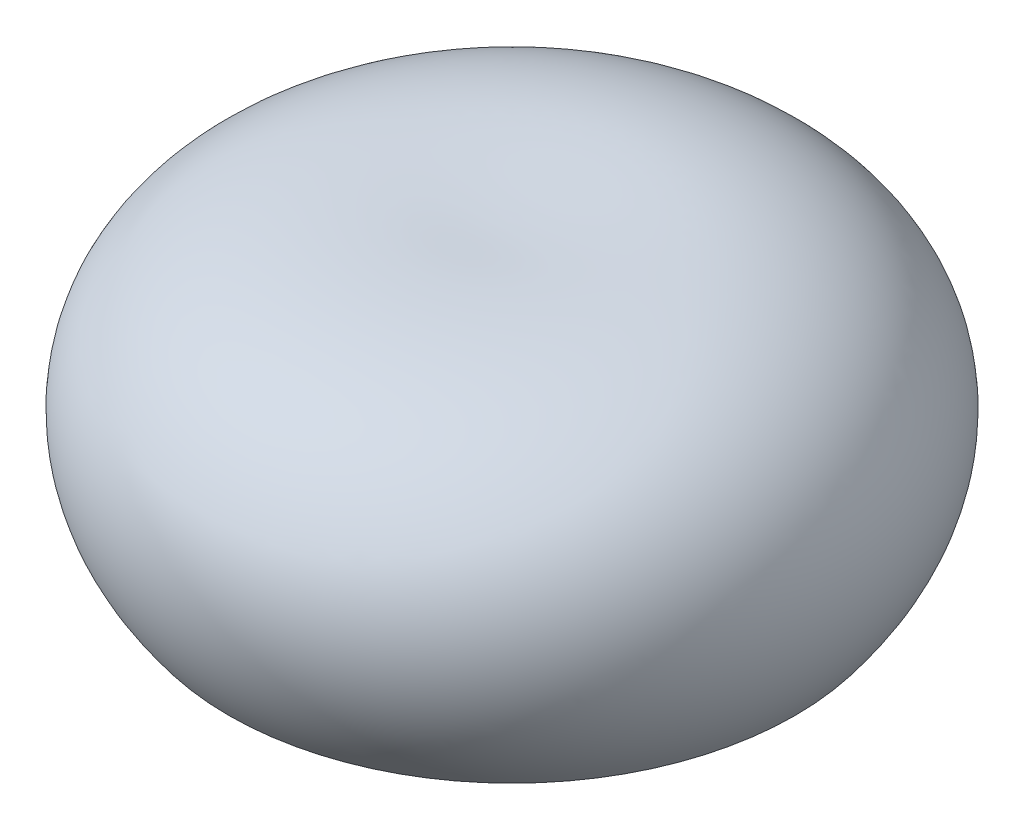
SolidWorks part; units mm, degrees
ref_plane "前视基准面" through (0, 0, 0) normal (0, 0, 1) x (1, 0, 0)
ref_plane "上视基准面" through (0, 0, 0) normal (0, 1, 0) x (1, 0, 0)
ref_plane "右视基准面" through (0, 0, 0) normal (1, 0, 0) x (0, 0, -1)
curve "曲线1"
  spline degree 3 poles (0, 7, 0) (0.0738, 6.9996, 0) (0.1783, 6.9991, 0) (0.3064, 7.0012, 0) (0.3805, 7.0029, 0) (0.4416, 7.0045, 0) (0.495, 7.0061, 0) (0.5432, 7.0077, 0) (0.5875, 7.0093, 0) (0.6288, 7.0109, 0) (0.6676, 7.0125, 0) (0.7044, 7.0141, 0) (0.7394, 7.0157, 0) (0.7729, 7.0172, 0) (0.8051, 7.0187, 0) (0.8362, 7.0203, 0) (0.8662, 7.0218, 0) (0.8953, 7.0233, 0) (0.9235, 7.0247, 0) (0.951, 7.0262, 0) (0.9778, 7.0276, 0) (1.004, 7.0291, 0) (1.0295, 7.0305, 0) (1.0545, 7.0319, 0) (1.079, 7.0333, 0) (1.103, 7.0346, 0) (1.1265, 7.036, 0) (1.1496, 7.0373, 0) (1.1724, 7.0386, 0) (1.1947, 7.0399, 0) (1.2167, 7.0412, 0) (1.2384, 7.0425, 0) (1.2598, 7.0438, 0) (1.2808, 7.045, 0) (1.3016, 7.0462, 0) (1.3221, 7.0474, 0) (1.3423, 7.0486, 0) (1.3623, 7.0498, 0) (1.382, 7.051, 0) (1.4015, 7.0521, 0) (1.4208, 7.0533, 0) (1.4399, 7.0544, 0) (1.4588, 7.0555, 0) (1.4775, 7.0566, 0) (1.496, 7.0577, 0) (1.5143, 7.0587, 0) (1.5324, 7.0598, 0) (1.5504, 7.0608, 0) (1.5682, 7.0618, 0) (1.5859, 7.0628, 0) (1.6034, 7.0638, 0) (1.6207, 7.0648, 0) (1.6379, 7.0657, 0) (1.655, 7.0667, 0) (1.672, 7.0676, 0) (1.6888, 7.0685, 0) (1.7054, 7.0694, 0) (1.722, 7.0703, 0) (1.7385, 7.0712, 0) (1.7548, 7.072, 0) (1.771, 7.0728, 0) (1.7871, 7.0737, 0) (1.8031, 7.0745, 0) (1.819, 7.0753, 0) (1.8348, 7.0761, 0) (1.8505, 7.0768, 0) (1.8661, 7.0776, 0) (1.8816, 7.0783, 0) (1.897, 7.079, 0) (1.9123, 7.0797, 0) (1.9275, 7.0804, 0) (1.9427, 7.0811, 0) (1.9578, 7.0818, 0) (1.9727, 7.0824, 0) (1.9876, 7.0831, 0) (2.0025, 7.0837, 0) (2.0172, 7.0843, 0) (2.0319, 7.0849, 0) (2.0465, 7.0855, 0) (2.061, 7.0861, 0) (2.0755, 7.0866, 0) (2.0899, 7.0872, 0) (2.1042, 7.0877, 0) (2.1184, 7.0882, 0) (2.1326, 7.0887, 0) (2.1468, 7.0892, 0) (2.1608, 7.0896, 0) (2.1748, 7.0901, 0) (2.1888, 7.0905, 0) (2.2027, 7.091, 0) (2.2165, 7.0914, 0) (2.2302, 7.0918, 0) (2.244, 7.0922, 0) (2.2576, 7.0925, 0) (2.2712, 7.0929, 0) (2.2848, 7.0933, 0) (2.2983, 7.0936, 0) (2.3117, 7.0939, 0) (2.3251, 7.0942, 0) (2.3385, 7.0945, 0) (2.3518, 7.0948, 0) (2.365, 7.095, 0) (2.3782, 7.0953, 0) (2.3914, 7.0955, 0) (2.4045, 7.0958, 0) (2.4175, 7.096, 0) (2.4305, 7.0962, 0) (2.4435, 7.0964, 0) (2.4565, 7.0965, 0) (2.4693, 7.0967, 0) (2.4822, 7.0968, 0) (2.495, 7.097, 0) (2.5078, 7.0971, 0) (2.5205, 7.0972, 0) (2.5332, 7.0973, 0) (2.5458, 7.0974, 0) (2.5584, 7.0974, 0) (2.571, 7.0975, 0) (2.5835, 7.0975, 0) (2.596, 7.0975, 0) (2.6085, 7.0975, 0) (2.6209, 7.0975, 0) (2.6333, 7.0975, 0) (2.6457, 7.0975, 0) (2.658, 7.0975, 0) (2.6703, 7.0974, 0) (2.6825, 7.0973, 0) (2.6948, 7.0973, 0) (2.7069, 7.0972, 0) (2.7191, 7.0971, 0) (2.7312, 7.0969, 0) (2.7433, 7.0968, 0) (2.7554, 7.0967, 0) (2.7674, 7.0965, 0) (2.7794, 7.0963, 0) (2.7914, 7.0962, 0) (2.8033, 7.096, 0) (2.8152, 7.0958, 0) (2.8271, 7.0955, 0) (2.8389, 7.0953, 0) (2.8508, 7.095, 0) (2.8625, 7.0948, 0) (2.8743, 7.0945, 0) (2.8861, 7.0942, 0) (2.8978, 7.0939, 0) (2.9094, 7.0936, 0) (2.9211, 7.0933, 0) (2.9327, 7.093, 0) (2.9443, 7.0926, 0) (2.9559, 7.0922, 0) (2.9675, 7.0919, 0) (2.979, 7.0915, 0) (2.9905, 7.0911, 0) (3.002, 7.0907, 0) (3.0134, 7.0902, 0) (3.0249, 7.0898, 0) (3.0363, 7.0893, 0) (3.0477, 7.0889, 0) (3.059, 7.0884, 0) (3.0704, 7.0879, 0) (3.0817, 7.0874, 0) (3.093, 7.0869, 0) (3.1042, 7.0864, 0) (3.1155, 7.0858, 0) (3.1267, 7.0853, 0) (3.1379, 7.0847, 0) (3.1491, 7.0841, 0) (3.1602, 7.0835, 0) (3.1714, 7.0829, 0) (3.1825, 7.0823, 0) (3.1936, 7.0817, 0) (3.2047, 7.0811, 0) (3.2157, 7.0804, 0) (3.2267, 7.0797, 0) (3.2378, 7.0791, 0) (3.2488, 7.0784, 0) (3.2597, 7.0777, 0) (3.2707, 7.0769, 0) (3.2816, 7.0762, 0) (3.2925, 7.0755, 0) (3.3034, 7.0747, 0) (3.3143, 7.074, 0) (3.3252, 7.0732, 0) (3.336, 7.0724, 0) (3.3468, 7.0716, 0) (3.3576, 7.0708, 0) (3.3684, 7.0699, 0) (3.3792, 7.0691, 0) (3.3899, 7.0683, 0) (3.4006, 7.0674, 0) (3.4113, 7.0665, 0) (3.422, 7.0656, 0) (3.4327, 7.0647, 0) (3.4434, 7.0638, 0) (3.454, 7.0629, 0) (3.4646, 7.0619, 0) (3.4752, 7.061, 0) (3.4858, 7.06, 0) (3.4964, 7.059, 0) (3.507, 7.0581, 0) (3.5175, 7.0571, 0) (3.528, 7.056, 0) (3.5385, 7.055, 0) (3.549, 7.054, 0) (3.5595, 7.0529, 0) (3.5699, 7.0519, 0) (3.5804, 7.0508, 0) (3.5908, 7.0497, 0) (3.6012, 7.0486, 0) (3.6116, 7.0475, 0) (3.622, 7.0464, 0) (3.6324, 7.0452, 0) (3.6427, 7.0441, 0) (3.6531, 7.0429, 0) (3.6634, 7.0417, 0) (3.6737, 7.0406, 0) (3.684, 7.0394, 0) (3.6942, 7.0381, 0) (3.7045, 7.0369, 0) (3.7148, 7.0357, 0) (3.725, 7.0344, 0) (3.7352, 7.0332, 0) (3.7454, 7.0319, 0) (3.7556, 7.0306, 0) (3.7658, 7.0293, 0) (3.7759, 7.028, 0) (3.7861, 7.0267, 0) (3.7962, 7.0254, 0) (3.8063, 7.024, 0) (3.8164, 7.0227, 0) (3.8265, 7.0213, 0) (3.8366, 7.0199, 0) (3.8467, 7.0185, 0) (3.8567, 7.0171, 0) (3.8668, 7.0157, 0) (3.8768, 7.0142, 0) (3.8868, 7.0128, 0) (3.8968, 7.0113, 0) (3.9068, 7.0099, 0) (3.9168, 7.0084, 0) (3.9267, 7.0069, 0) (3.9367, 7.0054, 0) (3.9466, 7.0039, 0) (3.9565, 7.0024, 0) (3.9665, 7.0008, 0) (3.9764, 6.9993, 0) (3.9862, 6.9977, 0) (3.9961, 6.9961, 0) (4.006, 6.9945, 0) (4.0158, 6.9929, 0) (4.0257, 6.9913, 0) (4.0355, 6.9897, 0) (4.0453, 6.988, 0) (4.0551, 6.9864, 0) (4.0649, 6.9847, 0) (4.0747, 6.983, 0) (4.0844, 6.9813, 0) (4.0942, 6.9796, 0) (4.1039, 6.9779, 0) (4.1136, 6.9762, 0) (4.1234, 6.9745, 0) (4.1331, 6.9727, 0) (4.1428, 6.971, 0) (4.1524, 6.9692, 0) (4.1621, 6.9674, 0) (4.1718, 6.9656, 0) (4.1814, 6.9638, 0) (4.1911, 6.962, 0) (4.2007, 6.9601, 0) (4.2103, 6.9583, 0) (4.2199, 6.9564, 0) (4.2295, 6.9545, 0) (4.2391, 6.9527, 0) (4.2486, 6.9508, 0) (4.2582, 6.9488, 0) (4.2677, 6.9469, 0) (4.2773, 6.945, 0) (4.2868, 6.943, 0) (4.2963, 6.9411, 0) (4.3058, 6.9391, 0) (4.3153, 6.9371, 0) (4.3248, 6.9351, 0) (4.3343, 6.9331, 0) (4.3437, 6.9311, 0) (4.3532, 6.9291, 0) (4.3626, 6.927, 0) (4.3721, 6.925, 0) (4.3815, 6.9229, 0) (4.3909, 6.9208, 0) (4.4003, 6.9187, 0) (4.4097, 6.9166, 0) (4.4191, 6.9145, 0) (4.4284, 6.9123, 0) (4.4378, 6.9102, 0) (4.4471, 6.908, 0) (4.4565, 6.9059, 0) (4.4658, 6.9037, 0) (4.4751, 6.9015, 0) (4.4844, 6.8993, 0) (4.4937, 6.8971, 0) (4.503, 6.8948, 0) (4.5123, 6.8926, 0) (4.5215, 6.8903, 0) (4.5308, 6.8881, 0) (4.54, 6.8858, 0) (4.5493, 6.8835, 0) (4.5585, 6.8812, 0) (4.5677, 6.8789, 0) (4.5769, 6.8765, 0) (4.5861, 6.8742, 0) (4.5953, 6.8718, 0) (4.6045, 6.8695, 0) (4.6136, 6.8671, 0) (4.6228, 6.8647, 0) (4.6319, 6.8623, 0) (4.6411, 6.8599, 0) (4.6502, 6.8575, 0) (4.6593, 6.855, 0) (4.6684, 6.8526, 0) (4.6775, 6.8501, 0) (4.6866, 6.8476, 0) (4.6957, 6.8451, 0) (4.7048, 6.8426, 0) (4.7138, 6.8401, 0) (4.7229, 6.8376, 0) (4.7319, 6.835, 0) (4.741, 6.8325, 0) (4.75, 6.8299, 0) (4.759, 6.8273, 0) (4.768, 6.8247, 0) (4.777, 6.8221, 0) (4.786, 6.8195, 0) (4.795, 6.8169, 0) (4.8039, 6.8142, 0) (4.8129, 6.8116, 0) (4.8218, 6.8089, 0) (4.8308, 6.8062, 0) (4.8397, 6.8035, 0) (4.8486, 6.8008, 0) (4.8575, 6.7981, 0) (4.8664, 6.7954, 0) (4.8753, 6.7926, 0) (4.8842, 6.7899, 0) (4.8931, 6.7871, 0) (4.902, 6.7843, 0) (4.9108, 6.7815, 0) (4.9197, 6.7787, 0) (4.9285, 6.7759, 0) (4.9373, 6.7731, 0) (4.9462, 6.7702, 0) (4.955, 6.7673, 0) (4.9638, 6.7645, 0) (4.9726, 6.7616, 0) (4.9813, 6.7587, 0) (4.9901, 6.7558, 0) (4.9989, 6.7529, 0) (5.0076, 6.7499, 0) (5.0164, 6.747, 0) (5.0251, 6.744, 0) (5.0339, 6.7411, 0) (5.0426, 6.7381, 0) (5.0513, 6.7351, 0) (5.06, 6.7321, 0) (5.0687, 6.729, 0) (5.0774, 6.726, 0) (5.0861, 6.7229, 0) (5.0947, 6.7199, 0) (5.1034, 6.7168, 0) (5.112, 6.7137, 0) (5.1207, 6.7106, 0) (5.1293, 6.7075, 0) (5.1379, 6.7044, 0) (5.1465, 6.7012, 0) (5.1552, 6.6981, 0) (5.1638, 6.6949, 0) (5.1723, 6.6917, 0) (5.1809, 6.6885, 0) (5.1895, 6.6853, 0) (5.1981, 6.6821, 0) (5.2066, 6.6789, 0) (5.2151, 6.6756, 0) (5.2237, 6.6724, 0) (5.2322, 6.6691, 0) (5.2407, 6.6658, 0) (5.2492, 6.6625, 0) (5.2577, 6.6592, 0) (5.2662, 6.6559, 0) (5.2747, 6.6526, 0) (5.2832, 6.6492, 0) (5.2917, 6.6459, 0) (5.3001, 6.6425, 0) (5.3086, 6.6391, 0) (5.317, 6.6357, 0) (5.3254, 6.6323, 0) (5.3338, 6.6289, 0) (5.3423, 6.6254, 0) (5.3507, 6.622, 0) (5.3591, 6.6185, 0) (5.3674, 6.615, 0) (5.3758, 6.6115, 0) (5.3842, 6.608, 0) (5.3926, 6.6045, 0) (5.4009, 6.601, 0) (5.4092, 6.5974, 0) (5.4176, 6.5939, 0) (5.4259, 6.5903, 0) (5.4342, 6.5867, 0) (5.4425, 6.5831, 0) (5.4508, 6.5795, 0) (5.4591, 6.5759, 0) (5.4674, 6.5722, 0) (5.4757, 6.5686, 0) (5.4839, 6.5649, 0) (5.4922, 6.5612, 0) (5.5004, 6.5576, 0) (5.5087, 6.5538, 0) (5.5169, 6.5501, 0) (5.5251, 6.5464, 0) (5.5333, 6.5427, 0) (5.5415, 6.5389, 0) (5.5497, 6.5351, 0) (5.5579, 6.5313, 0) (5.5661, 6.5275, 0) (5.5743, 6.5237, 0) (5.5824, 6.5199, 0) (5.5906, 6.5161, 0) (5.5987, 6.5122, 0) (5.6069, 6.5083, 0) (5.615, 6.5045, 0) (5.6231, 6.5006, 0) (5.6312, 6.4967, 0) (5.6393, 6.4927, 0) (5.6474, 6.4888, 0) (5.6555, 6.4849, 0) (5.6635, 6.4809, 0) (5.6716, 6.4769, 0) (5.6796, 6.4729, 0) (5.6877, 6.4689, 0) (5.6957, 6.4649, 0) (5.7038, 6.4609, 0) (5.7118, 6.4568, 0) (5.7198, 6.4528, 0) (5.7278, 6.4487, 0) (5.7358, 6.4446, 0) (5.7438, 6.4405, 0) (5.7517, 6.4364, 0) (5.7597, 6.4323, 0) (5.7676, 6.4282, 0) (5.7756, 6.424, 0) (5.7835, 6.4198, 0) (5.7915, 6.4157, 0) (5.7994, 6.4115, 0) (5.8073, 6.4073, 0) (5.8152, 6.403, 0) (5.8231, 6.3988, 0) (5.831, 6.3945, 0) (5.8388, 6.3903, 0) (5.8467, 6.386, 0) (5.8546, 6.3817, 0) (5.8624, 6.3774, 0) (5.8703, 6.3731, 0) (5.8781, 6.3687, 0) (5.8859, 6.3644, 0) (5.8937, 6.36, 0) (5.9015, 6.3557, 0) (5.9093, 6.3513, 0) (5.9171, 6.3469, 0) (5.9249, 6.3424, 0) (5.9326, 6.338, 0) (5.9404, 6.3336, 0) (5.9481, 6.3291, 0) (5.9559, 6.3246, 0) (5.9636, 6.3201, 0) (5.9713, 6.3156, 0) (5.979, 6.3111, 0) (5.9867, 6.3066, 0) (5.9944, 6.302, 0) (6.0021, 6.2975, 0) (6.0098, 6.2929, 0) (6.0175, 6.2883, 0) (6.0251, 6.2837, 0) (6.0328, 6.2791, 0) (6.0404, 6.2745, 0) (6.048, 6.2698, 0) (6.0556, 6.2652, 0) (6.0633, 6.2605, 0) (6.0709, 6.2558, 0) (6.0784, 6.2511, 0) (6.086, 6.2464, 0) (6.0936, 6.2416, 0) (6.1012, 6.2369, 0) (6.1087, 6.2321, 0) (6.1163, 6.2274, 0) (6.1238, 6.2226, 0) (6.1313, 6.2178, 0) (6.1388, 6.2129, 0) (6.1463, 6.2081, 0) (6.1538, 6.2033, 0) (6.1613, 6.1984, 0) (6.1688, 6.1935, 0) (6.1763, 6.1886, 0) (6.1837, 6.1837, 0) (6.1912, 6.1788, 0) (6.1986, 6.1739, 0) (6.206, 6.1689, 0) (6.2134, 6.1639, 0) (6.2208, 6.159, 0) (6.2282, 6.154, 0) (6.2356, 6.1489, 0) (6.243, 6.1439, 0) (6.2504, 6.1389, 0) (6.2577, 6.1338, 0) (6.2651, 6.1287, 0) (6.2724, 6.1237, 0) (6.2798, 6.1186, 0) (6.2871, 6.1134, 0) (6.2944, 6.1083, 0) (6.3017, 6.1032, 0) (6.309, 6.098, 0) (6.3163, 6.0928, 0) (6.3235, 6.0876, 0) (6.3308, 6.0824, 0) (6.3381, 6.0772, 0) (6.3453, 6.072, 0) (6.3525, 6.0667, 0) (6.3598, 6.0615, 0) (6.367, 6.0562, 0) (6.3742, 6.0509, 0) (6.3814, 6.0456, 0) (6.3885, 6.0403, 0) (6.3957, 6.0349, 0) (6.4029, 6.0296, 0) (6.41, 6.0242, 0) (6.4172, 6.0188, 0) (6.4243, 6.0134, 0) (6.4314, 6.008, 0) (6.4385, 6.0025, 0) (6.4456, 5.9971, 0) (6.4527, 5.9916, 0) (6.4598, 5.9861, 0) (6.4668, 5.9806, 0) (6.4739, 5.9751, 0) (6.4809, 5.9696, 0) (6.488, 5.9641, 0) (6.495, 5.9585, 0) (6.502, 5.9529, 0) (6.509, 5.9473, 0) (6.516, 5.9417, 0) (6.523, 5.9361, 0) (6.53, 5.9305, 0) (6.5369, 5.9248, 0) (6.5439, 5.9192, 0) (6.5508, 5.9135, 0) (6.5578, 5.9078, 0) (6.5647, 5.9021, 0) (6.5716, 5.8963, 0) (6.5785, 5.8906, 0) (6.5854, 5.8848, 0) (6.5922, 5.8791, 0) (6.5991, 5.8733, 0) (6.606, 5.8675, 0) (6.6128, 5.8616, 0) (6.6196, 5.8558, 0) (6.6265, 5.8499, 0) (6.6333, 5.8441, 0) (6.6401, 5.8382, 0) (6.6469, 5.8323, 0) (6.6536, 5.8263, 0) (6.6604, 5.8204, 0) (6.6672, 5.8144, 0) (6.6739, 5.8085, 0) (6.6806, 5.8025, 0) (6.6874, 5.7965, 0) (6.6941, 5.7905, 0) (6.7008, 5.7844, 0) (6.7074, 5.7784, 0) (6.7141, 5.7723, 0) (6.7208, 5.7662, 0) (6.7274, 5.7601, 0) (6.7341, 5.754, 0) (6.7407, 5.7479, 0) (6.7473, 5.7417, 0) (6.7539, 5.7356, 0) (6.7605, 5.7294, 0) (6.7671, 5.7232, 0) (6.7737, 5.717, 0) (6.7802, 5.7107, 0) (6.7868, 5.7045, 0) (6.7933, 5.6982, 0) (6.7998, 5.6919, 0) (6.8064, 5.6856, 0) (6.8129, 5.6793, 0) (6.8194, 5.673, 0) (6.8258, 5.6666, 0) (6.8323, 5.6603, 0) (6.8387, 5.6539, 0) (6.8452, 5.6475, 0) (6.8516, 5.6411, 0) (6.858, 5.6346, 0) (6.8644, 5.6282, 0) (6.8708, 5.6217, 0) (6.8772, 5.6152, 0) (6.8836, 5.6087, 0) (6.8899, 5.6022, 0) (6.8963, 5.5957, 0) (6.9026, 5.5891, 0) (6.9089, 5.5825, 0) (6.9152, 5.5759, 0) (6.9215, 5.5693, 0) (6.9278, 5.5627, 0) (6.9341, 5.5561, 0) (6.9403, 5.5494, 0) (6.9466, 5.5427, 0) (6.9528, 5.5361, 0) (6.959, 5.5293, 0) (6.9652, 5.5226, 0) (6.9714, 5.5159, 0) (6.9776, 5.5091, 0) (6.9838, 5.5023, 0) (6.9899, 5.4955, 0) (6.9961, 5.4887, 0) (7.0022, 5.4819, 0) (7.0083, 5.475, 0) (7.0144, 5.4682, 0) (7.0205, 5.4613, 0) (7.0266, 5.4544, 0) (7.0326, 5.4475, 0) (7.0387, 5.4405, 0) (7.0447, 5.4336, 0) (7.0507, 5.4266, 0) (7.0568, 5.4196, 0) (7.0627, 5.4126, 0) (7.0687, 5.4055, 0) (7.0747, 5.3985, 0) (7.0807, 5.3914, 0) (7.0866, 5.3844, 0) (7.0925, 5.3772, 0) (7.0984, 5.3701, 0) (7.1043, 5.363, 0) (7.1102, 5.3558, 0) (7.1161, 5.3487, 0) (7.122, 5.3415, 0) (7.1278, 5.3343, 0) (7.1336, 5.327, 0) (7.1395, 5.3198, 0) (7.1453, 5.3125, 0) (7.151, 5.3052, 0) (7.1568, 5.2979, 0) (7.1626, 5.2906, 0) (7.1683, 5.2833, 0) (7.1741, 5.2759, 0) (7.1798, 5.2685, 0) (7.1855, 5.2611, 0) (7.1912, 5.2537, 0) (7.1968, 5.2463, 0) (7.2025, 5.2388, 0) (7.2082, 5.2313, 0) (7.2138, 5.2238, 0) (7.2194, 5.2163, 0) (7.225, 5.2088, 0) (7.2306, 5.2013, 0) (7.2362, 5.1937, 0) (7.2417, 5.1861, 0) (7.2473, 5.1785, 0) (7.2528, 5.1709, 0) (7.2583, 5.1632, 0) (7.2638, 5.1556, 0) (7.2693, 5.1479, 0) (7.2748, 5.1402, 0) (7.2802, 5.1324, 0) (7.2856, 5.1247, 0) (7.2911, 5.1169, 0) (7.2965, 5.1092, 0) (7.3019, 5.1014, 0) (7.3072, 5.0935, 0) (7.3126, 5.0857, 0) (7.3179, 5.0778, 0) (7.3233, 5.0699, 0) (7.3286, 5.062, 0) (7.3339, 5.0541, 0) (7.3391, 5.0462, 0) (7.3444, 5.0382, 0) (7.3497, 5.0302, 0) (7.3549, 5.0222, 0) (7.3601, 5.0142, 0) (7.3653, 5.0062, 0) (7.3705, 4.9981, 0) (7.3757, 4.99, 0) (7.3808, 4.9819, 0) (7.3859, 4.9738, 0) (7.3911, 4.9657, 0) (7.3962, 4.9575, 0) (7.4012, 4.9493, 0) (7.4063, 4.9411, 0) (7.4114, 4.9329, 0) (7.4164, 4.9246, 0) (7.4214, 4.9164, 0) (7.4264, 4.9081, 0) (7.4314, 4.8998, 0) (7.4364, 4.8914, 0) (7.4413, 4.8831, 0) (7.4462, 4.8747, 0) (7.4512, 4.8663, 0) (7.4561, 4.8579, 0) (7.4609, 4.8495, 0) (7.4658, 4.841, 0) (7.4706, 4.8325, 0) (7.4755, 4.824, 0) (7.4803, 4.8155, 0) (7.4851, 4.807, 0) (7.4899, 4.7984, 0) (7.4946, 4.7898, 0) (7.4993, 4.7812, 0) (7.5041, 4.7726, 0) (7.5088, 4.7639, 0) (7.5134, 4.7552, 0) (7.5181, 4.7465, 0) (7.5228, 4.7378, 0) (7.5274, 4.7291, 0) (7.532, 4.7203, 0) (7.5366, 4.7115, 0) (7.5412, 4.7027, 0) (7.5457, 4.6939, 0) (7.5503, 4.6851, 0) (7.5548, 4.6762, 0) (7.5593, 4.6673, 0) (7.5637, 4.6584, 0) (7.5682, 4.6494, 0) (7.5726, 4.6405, 0) (7.5771, 4.6315, 0) (7.5815, 4.6225, 0) (7.5858, 4.6134, 0) (7.5902, 4.6044, 0) (7.5945, 4.5953, 0) (7.5989, 4.5862, 0) (7.6032, 4.5771, 0) (7.6075, 4.5679, 0) (7.6117, 4.5587, 0) (7.616, 4.5495, 0) (7.6202, 4.5403, 0) (7.6244, 4.5311, 0) (7.6286, 4.5218, 0) (7.6327, 4.5125, 0) (7.6369, 4.5032, 0) (7.641, 4.4939, 0) (7.6451, 4.4845, 0) (7.6492, 4.4751, 0) (7.6532, 4.4657, 0) (7.6573, 4.4563, 0) (7.6613, 4.4468, 0) (7.6653, 4.4373, 0) (7.6692, 4.4278, 0) (7.6732, 4.4183, 0) (7.6771, 4.4087, 0) (7.681, 4.3992, 0) (7.6849, 4.3896, 0) (7.6888, 4.3799, 0) (7.6926, 4.3703, 0) (7.6964, 4.3606, 0) (7.7002, 4.3509, 0) (7.704, 4.3411, 0) (7.7078, 4.3314, 0) (7.7115, 4.3216, 0) (7.7152, 4.3118, 0) (7.7189, 4.302, 0) (7.7226, 4.2921, 0) (7.7262, 4.2822, 0) (7.7298, 4.2723, 0) (7.7334, 4.2624, 0) (7.737, 4.2524, 0) (7.7405, 4.2424, 0) (7.744, 4.2324, 0) (7.7475, 4.2223, 0) (7.751, 4.2123, 0) (7.7545, 4.2022, 0) (7.7579, 4.1921, 0) (7.7613, 4.1819, 0) (7.7647, 4.1717, 0) (7.768, 4.1615, 0) (7.7714, 4.1513, 0) (7.7747, 4.141, 0) (7.778, 4.1308, 0) (7.7812, 4.1204, 0) (7.7845, 4.1101, 0) (7.7877, 4.0997, 0) (7.7908, 4.0893, 0) (7.794, 4.0789, 0) (7.7971, 4.0685, 0) (7.8002, 4.058, 0) (7.8033, 4.0475, 0) (7.8064, 4.0369, 0) (7.8094, 4.0264, 0) (7.8124, 4.0158, 0) (7.8154, 4.0051, 0) (7.8183, 3.9945, 0) (7.8212, 3.9838, 0) (7.8241, 3.9731, 0) (7.827, 3.9624, 0) (7.8298, 3.9516, 0) (7.8327, 3.9408, 0) (7.8354, 3.93, 0) (7.8382, 3.9191, 0) (7.8409, 3.9082, 0) (7.8436, 3.8973, 0) (7.8463, 3.8863, 0) (7.849, 3.8754, 0) (7.8516, 3.8643, 0) (7.8542, 3.8533, 0) (7.8567, 3.8422, 0) (7.8593, 3.8311, 0) (7.8618, 3.82, 0) (7.8642, 3.8088, 0) (7.8667, 3.7976, 0) (7.8691, 3.7864, 0) (7.8715, 3.7751, 0) (7.8738, 3.7638, 0) (7.8762, 3.7525, 0) (7.8785, 3.7411, 0) (7.8807, 3.7297, 0) (7.883, 3.7183, 0) (7.8852, 3.7069, 0) (7.8873, 3.6954, 0) (7.8895, 3.6838, 0) (7.8916, 3.6723, 0) (7.8937, 3.6607, 0) (7.8957, 3.6491, 0) (7.8977, 3.6374, 0) (7.8997, 3.6257, 0) (7.9016, 3.614, 0) (7.9036, 3.6022, 0) (7.9054, 3.5904, 0) (7.9073, 3.5786, 0) (7.9091, 3.5667, 0) (7.9109, 3.5548, 0) (7.9126, 3.5429, 0) (7.9144, 3.5309, 0) (7.916, 3.5189, 0) (7.9177, 3.5068, 0) (7.9193, 3.4947, 0) (7.9209, 3.4826, 0) (7.9224, 3.4705, 0) (7.9239, 3.4583, 0) (7.9254, 3.446, 0) (7.9268, 3.4338, 0) (7.9282, 3.4214, 0) (7.9296, 3.4091, 0) (7.9309, 3.3967, 0) (7.9322, 3.3843, 0) (7.9334, 3.3718, 0) (7.9346, 3.3593, 0) (7.9358, 3.3468, 0) (7.9369, 3.3342, 0) (7.938, 3.3215, 0) (7.9391, 3.3089, 0) (7.9401, 3.2962, 0) (7.9411, 3.2834, 0) (7.942, 3.2706, 0) (7.9429, 3.2578, 0) (7.9438, 3.2449, 0) (7.9446, 3.232, 0) (7.9454, 3.219, 0) (7.9461, 3.206, 0) (7.9468, 3.193, 0) (7.9475, 3.1799, 0) (7.9481, 3.1668, 0) (7.9486, 3.1536, 0) (7.9492, 3.1403, 0) (7.9496, 3.1271, 0) (7.9501, 3.1138, 0) (7.9505, 3.1004, 0) (7.9508, 3.087, 0) (7.9511, 3.0735, 0) (7.9514, 3.06, 0) (7.9516, 3.0465, 0) (7.9517, 3.0329, 0) (7.9518, 3.0192, 0) (7.9519, 3.0055, 0) (7.9519, 2.9918, 0) (7.9519, 2.978, 0) (7.9518, 2.9641, 0) (7.9517, 2.9502, 0) (7.9515, 2.9363, 0) (7.9513, 2.9223, 0) (7.951, 2.9082, 0) (7.9507, 2.8941, 0) (7.9503, 2.88, 0) (7.9499, 2.8657, 0) (7.9494, 2.8515, 0) (7.9489, 2.8371, 0) (7.9483, 2.8228, 0) (7.9477, 2.8083, 0) (7.947, 2.7938, 0) (7.9462, 2.7793, 0) (7.9454, 2.7647, 0) (7.9445, 2.75, 0) (7.9436, 2.7353, 0) (7.9426, 2.7205, 0) (7.9416, 2.7056, 0) (7.9405, 2.6907, 0) (7.9393, 2.6757, 0) (7.9381, 2.6607, 0) (7.9368, 2.6456, 0) (7.9355, 2.6304, 0) (7.9341, 2.6152, 0) (7.9326, 2.5999, 0) (7.9311, 2.5845, 0) (7.9295, 2.5691, 0) (7.9278, 2.5536, 0) (7.9261, 2.538, 0) (7.9243, 2.5224, 0) (7.9224, 2.5066, 0) (7.9205, 2.4909, 0) (7.9185, 2.475, 0) (7.9164, 2.459, 0) (7.9143, 2.443, 0) (7.912, 2.4269, 0) (7.9097, 2.4108, 0) (7.9074, 2.3945, 0) (7.9049, 2.3782, 0) (7.9024, 2.3618, 0) (7.8998, 2.3453, 0) (7.8971, 2.3287, 0) (7.8943, 2.312, 0) (7.8915, 2.2953, 0) (7.8885, 2.2784, 0) (7.8855, 2.2615, 0) (7.8824, 2.2445, 0) (7.8792, 2.2273, 0) (7.8759, 2.2101, 0) (7.8725, 2.1928, 0) (7.8691, 2.1754, 0) (7.8655, 2.1579, 0) (7.8618, 2.1403, 0) (7.8581, 2.1225, 0) (7.8542, 2.1047, 0) (7.8503, 2.0868, 0) (7.8462, 2.0687, 0) (7.842, 2.0506, 0) (7.8378, 2.0323, 0) (7.8334, 2.0139, 0) (7.8289, 1.9954, 0) (7.8243, 1.9767, 0) (7.8195, 1.9579, 0) (7.8147, 1.939, 0) (7.8097, 1.92, 0) (7.8046, 1.9008, 0) (7.7994, 1.8815, 0) (7.794, 1.8621, 0) (7.7885, 1.8425, 0) (7.7829, 1.8227, 0) (7.7771, 1.8028, 0) (7.7712, 1.7828, 0) (7.7652, 1.7626, 0) (7.759, 1.7422, 0) (7.7526, 1.7216, 0) (7.7461, 1.7009, 0) (7.7394, 1.6799, 0) (7.7325, 1.6588, 0) (7.7255, 1.6375, 0) (7.7182, 1.616, 0) (7.7108, 1.5943, 0) (7.7032, 1.5723, 0) (7.6954, 1.5502, 0) (7.6874, 1.5278, 0) (7.6792, 1.5051, 0) (7.6708, 1.4822, 0) (7.6621, 1.4591, 0) (7.6532, 1.4357, 0) (7.644, 1.412, 0) (7.6346, 1.388, 0) (7.6249, 1.3637, 0) (7.615, 1.3391, 0) (7.6047, 1.3141, 0) (7.5941, 1.2888, 0) (7.5833, 1.2631, 0) (7.572, 1.237, 0) (7.5604, 1.2105, 0) (7.5485, 1.1835, 0) (7.5361, 1.1561, 0) (7.5233, 1.1282, 0) (7.51, 1.0997, 0) (7.4963, 1.0707, 0) (7.482, 1.041, 0) (7.4672, 1.0107, 0) (7.4518, 0.9797, 0) (7.4357, 0.9478, 0) (7.4189, 0.9152, 0) (7.4013, 0.8815, 0) (7.3829, 0.8469, 0) (7.3635, 0.811, 0) (7.343, 0.7739, 0) (7.3212, 0.7352, 0) (7.2981, 0.6948, 0) (7.2732, 0.6523, 0) (7.2464, 0.6073, 0) (7.2172, 0.5594, 0) (7.1849, 0.5076, 0) (7.1485, 0.4506, 0) (7.1062, 0.386, 0) (7.0539, 0.3086, 0) (6.9626, 0.1779, 0) (6.8856, 0.0734, 0) (6.8314, 0, 0) knots 0 0 0 0 0.016508 0.023364 0.028636 0.033092 0.037026 0.040591 0.043877 0.046942 0.049828 0.052563 0.055171 0.057668 0.060068 0.062382 0.06462 0.066789 0.068896 0.070946 0.072944 0.074894 0.0768 0.078664 0.080491 0.082282 0.08404 0.085766 0.087463 0.089131 0.090774 0.092392 0.093986 0.095557 0.097107 0.098637 0.100147 0.101639 0.103112 0.104569 0.10601 0.107434 0.108844 0.110239 0.11162 0.112987 0.114341 0.115683 0.117013 0.118331 0.119637 0.120933 0.122218 0.123492 0.124757 0.126012 0.127257 0.128493 0.129721 0.130939 0.132149 0.133351 0.134545 0.135731 0.13691 0.138081 0.139245 0.140402 0.141552 0.142695 0.143832 0.144962 0.146086 0.147204 0.148315 0.149421 0.150522 0.151616 0.152705 0.153789 0.154868 0.155941 0.157009 0.158072 0.159131 0.160184 0.161233 0.162277 0.163317 0.164352 0.165383 0.16641 0.167433 0.168451 0.169465 0.170476 0.171482 0.172485 0.173483 0.174478 0.17547 0.176457 0.177442 0.178422 0.1794 0.180374 0.181344 0.182312 0.183276 0.184236 0.185194 0.186149 0.187101 0.188049 0.188995 0.189938 0.190877 0.191815 0.192749 0.19368 0.194609 0.195535 0.196459 0.19738 0.198298 0.199214 0.200127 0.201038 0.201946 0.202852 0.203756 0.204657 0.205556 0.206453 0.207347 0.208239 0.209129 0.210017 0.210902 0.211786 0.212667 0.213547 0.214424 0.215299 0.216172 0.217044 0.217913 0.21878 0.219646 0.220509 0.221371 0.222231 0.223089 0.223945 0.2248 0.225652 0.226503 0.227353 0.2282 0.229046 0.22989 0.230732 0.231573 0.232412 0.23325 0.234086 0.23492 0.235753 0.236585 0.237414 0.238243 0.239069 0.239895 0.240719 0.241541 0.242362 0.243182 0.244 0.244816 0.245632 0.246446 0.247258 0.24807 0.24888 0.249688 0.250496 0.251302 0.252106 0.25291 0.253712 0.254513 0.255313 0.256111 0.256909 0.257705 0.2585 0.259294 0.260086 0.260878 0.261668 0.262457 0.263245 0.264032 0.264818 0.265603 0.266386 0.267169 0.26795 0.268731 0.26951 0.270288 0.271066 0.271842 0.272617 0.273391 0.274165 0.274937 0.275708 0.276478 0.277248 0.278016 0.278784 0.27955 0.280316 0.28108 0.281844 0.282607 0.283369 0.28413 0.28489 0.285649 0.286407 0.287165 0.287921 0.288677 0.289432 0.290186 0.290939 0.291692 0.292444 0.293194 0.293944 0.294693 0.295442 0.296189 0.296936 0.297682 0.298428 0.299172 0.299916 0.300659 0.301401 0.302143 0.302883 0.303624 0.304363 0.305101 0.305839 0.306577 0.307313 0.308049 0.308784 0.309518 0.310252 0.310985 0.311718 0.312449 0.31318 0.313911 0.31464 0.31537 0.316098 0.316826 0.317553 0.31828 0.319006 0.319731 0.320456 0.32118 0.321903 0.322626 0.323349 0.32407 0.324791 0.325512 0.326232 0.326951 0.32767 0.328389 0.329106 0.329824 0.33054 0.331256 0.331972 0.332687 0.333401 0.334115 0.334829 0.335541 0.336254 0.336966 0.337677 0.338388 0.339098 0.339808 0.340517 0.341226 0.341934 0.342642 0.34335 0.344057 0.344763 0.345469 0.346174 0.346879 0.347584 0.348288 0.348992 0.349695 0.350398 0.3511 0.351802 0.352503 0.353204 0.353905 0.354605 0.355305 0.356004 0.356703 0.357401 0.3581 0.358797 0.359494 0.360191 0.360888 0.361584 0.362279 0.362975 0.36367 0.364364 0.365058 0.365752 0.366445 0.367138 0.367831 0.368523 0.369215 0.369907 0.370598 0.371289 0.371979 0.372669 0.373359 0.374049 0.374738 0.375427 0.376115 0.376803 0.377491 0.378178 0.378866 0.379552 0.380239 0.380925 0.381611 0.382297 0.382982 0.383667 0.384351 0.385036 0.38572 0.386404 0.387087 0.38777 0.388453 0.389136 0.389818 0.3905 0.391182 0.391863 0.392545 0.393226 0.393906 0.394587 0.395267 0.395947 0.396627 0.397306 0.397985 0.398664 0.399343 0.400021 0.400699 0.401377 0.402055 0.402733 0.40341 0.404087 0.404764 0.40544 0.406117 0.406793 0.407469 0.408144 0.40882 0.409495 0.41017 0.410845 0.41152 0.412194 0.412868 0.413542 0.414216 0.41489 0.415563 0.416237 0.41691 0.417583 0.418255 0.418928 0.4196 0.420273 0.420945 0.421616 0.422288 0.42296 0.423631 0.424302 0.424973 0.425644 0.426315 0.426986 0.427656 0.428326 0.428997 0.429667 0.430336 0.431006 0.431676 0.432345 0.433015 0.433684 0.434353 0.435022 0.435691 0.436359 0.437028 0.437696 0.438365 0.439033 0.439701 0.440369 0.441037 0.441705 0.442373 0.44304 0.443708 0.444375 0.445043 0.44571 0.446377 0.447044 0.447711 0.448378 0.449045 0.449711 0.450378 0.451045 0.451711 0.452378 0.453044 0.45371 0.454377 0.455043 0.455709 0.456375 0.457041 0.457707 0.458373 0.459039 0.459705 0.460371 0.461036 0.461702 0.462368 0.463034 0.463699 0.464365 0.46503 0.465696 0.466361 0.467027 0.467692 0.468358 0.469023 0.469689 0.470354 0.47102 0.471685 0.472351 0.473016 0.473681 0.474347 0.475012 0.475678 0.476343 0.477009 0.477674 0.47834 0.479005 0.479671 0.480336 0.481002 0.481668 0.482333 0.482999 0.483665 0.48433 0.484996 0.485662 0.486328 0.486994 0.48766 0.488326 0.488992 0.489658 0.490324 0.490991 0.491657 0.492324 0.49299 0.493657 0.494323 0.49499 0.495657 0.496324 0.496991 0.497658 0.498325 0.498992 0.499659 0.500327 0.500994 0.501662 0.50233 0.502997 0.503665 0.504333 0.505001 0.50567 0.506338 0.507007 0.507675 0.508344 0.509013 0.509682 0.510351 0.511021 0.51169 0.51236 0.513029 0.513699 0.514369 0.515039 0.51571 0.51638 0.517051 0.517722 0.518393 0.519064 0.519735 0.520407 0.521078 0.52175 0.522422 0.523095 0.523767 0.52444 0.525113 0.525786 0.526459 0.527132 0.527806 0.52848 0.529154 0.529828 0.530502 0.531177 0.531852 0.532527 0.533203 0.533878 0.534554 0.53523 0.535907 0.536583 0.53726 0.537937 0.538614 0.539292 0.53997 0.540648 0.541327 0.542005 0.542684 0.543363 0.544043 0.544723 0.545403 0.546083 0.546764 0.547445 0.548126 0.548808 0.549489 0.550172 0.550854 0.551537 0.55222 0.552904 0.553587 0.554271 0.554956 0.555641 0.556326 0.557011 0.557697 0.558383 0.55907 0.559757 0.560444 0.561132 0.56182 0.562508 0.563197 0.563886 0.564576 0.565266 0.565956 0.566647 0.567338 0.568029 0.568721 0.569414 0.570107 0.5708 0.571493 0.572188 0.572882 0.573577 0.574272 0.574968 0.575665 0.576361 0.577059 0.577756 0.578454 0.579153 0.579852 0.580552 0.581252 0.581952 0.582653 0.583355 0.584057 0.58476 0.585463 0.586166 0.586871 0.587575 0.58828 0.588986 0.589692 0.590399 0.591107 0.591815 0.592523 0.593232 0.593942 0.594652 0.595363 0.596074 0.596786 0.597499 0.598212 0.598926 0.59964 0.600355 0.601071 0.601787 0.602504 0.603222 0.60394 0.604659 0.605379 0.606099 0.60682 0.607541 0.608264 0.608987 0.60971 0.610435 0.61116 0.611885 0.612612 0.613339 0.614067 0.614796 0.615525 0.616255 0.616986 0.617718 0.61845 0.619183 0.619917 0.620652 0.621388 0.622124 0.622861 0.623599 0.624338 0.625078 0.625818 0.62656 0.627302 0.628045 0.628789 0.629534 0.630279 0.631026 0.631773 0.632522 0.633271 0.634021 0.634772 0.635524 0.636277 0.637031 0.637786 0.638542 0.639299 0.640056 0.640815 0.641575 0.642336 0.643098 0.64386 0.644624 0.645389 0.646155 0.646922 0.64769 0.648459 0.64923 0.650001 0.650773 0.651547 0.652322 0.653098 0.653875 0.654653 0.655432 0.656212 0.656994 0.657777 0.658561 0.659346 0.660133 0.66092 0.661709 0.662499 0.663291 0.664084 0.664878 0.665673 0.66647 0.667268 0.668067 0.668868 0.66967 0.670473 0.671278 0.672084 0.672892 0.673701 0.674511 0.675323 0.676136 0.676951 0.677768 0.678585 0.679405 0.680225 0.681048 0.681872 0.682697 0.683524 0.684353 0.685183 0.686015 0.686849 0.687684 0.688521 0.689359 0.690199 0.691041 0.691885 0.692731 0.693578 0.694427 0.695278 0.69613 0.696985 0.697841 0.698699 0.699559 0.700421 0.701285 0.702151 0.703018 0.703888 0.70476 0.705634 0.706509 0.707387 0.708267 0.709149 0.710033 0.710919 0.711808 0.712698 0.713591 0.714486 0.715384 0.716283 0.717185 0.718089 0.718996 0.719905 0.720816 0.721729 0.722646 0.723564 0.724485 0.725409 0.726335 0.727264 0.728195 0.729129 0.730066 0.731005 0.731947 0.732892 0.733839 0.734789 0.735743 0.736699 0.737658 0.738619 0.739584 0.740552 0.741523 0.742497 0.743474 0.744454 0.745438 0.746424 0.747414 0.748407 0.749404 0.750404 0.751407 0.752414 0.753424 0.754438 0.755455 0.756476 0.757501 0.758529 0.759562 0.760598 0.761638 0.762681 0.763729 0.764781 0.765837 0.766897 0.767962 0.76903 0.770103 0.77118 0.772262 0.773348 0.774439 0.775534 0.776634 0.777739 0.778849 0.779963 0.781083 0.782208 0.783337 0.784472 0.785613 0.786758 0.787909 0.789066 0.790228 0.791396 0.79257 0.79375 0.794936 0.796128 0.797326 0.79853 0.799741 0.800959 0.802183 0.803414 0.804652 0.805897 0.807149 0.808408 0.809675 0.81095 0.812232 0.813522 0.814821 0.816127 0.817442 0.818765 0.820098 0.821439 0.822789 0.824149 0.825518 0.826897 0.828286 0.829685 0.831095 0.832516 0.833947 0.83539 0.836844 0.83831 0.839789 0.841279 0.842783 0.8443 0.84583 0.847375 0.848933 0.850507 0.852096 0.8537 0.855321 0.856959 0.858613 0.860286 0.861977 0.863688 0.865418 0.867169 0.868942 0.870736 0.872554 0.874396 0.876263 0.878157 0.880078 0.882027 0.884007 0.886019 0.888063 0.890143 0.89226 0.894416 0.896614 0.898856 0.901145 0.903484 0.905877 0.908328 0.910841 0.913422 0.916077 0.918813 0.921638 0.924562 0.927596 0.930754 0.934054 0.937517 0.941171 0.945054 0.949215 0.953729 0.958707 0.964338 0.970988 0.979601 1 1 1 1
sketch "草图1" plane through (0, 0, 0) normal (0, 0, 1) x (1, 0, 0)
  line L0 (0, 7) -> (0, 0)
  line L1 (6.8314, 0) -> (0, 0)
  spline S0 degree 3 number of poles 1003 (0, 7) -> (6.8314, 0) construction
  spline S1 degree 3 number of poles 1003 (0, 7) -> (6.8314, 0)
revolve "旋转1" add sketch "草图1" angle 360 about L0
sketch "草图2" plane through (0, 0, 0) normal (0, -1, 0) x (1, 0, 0)
  line L0 (0, 5) -> (0, -5)
  arc A0 (0, -5) -> (0, 5) centre (0, 0) ccw
revolve "切除-旋转1" cut sketch "草图2" angle 360 about L0
